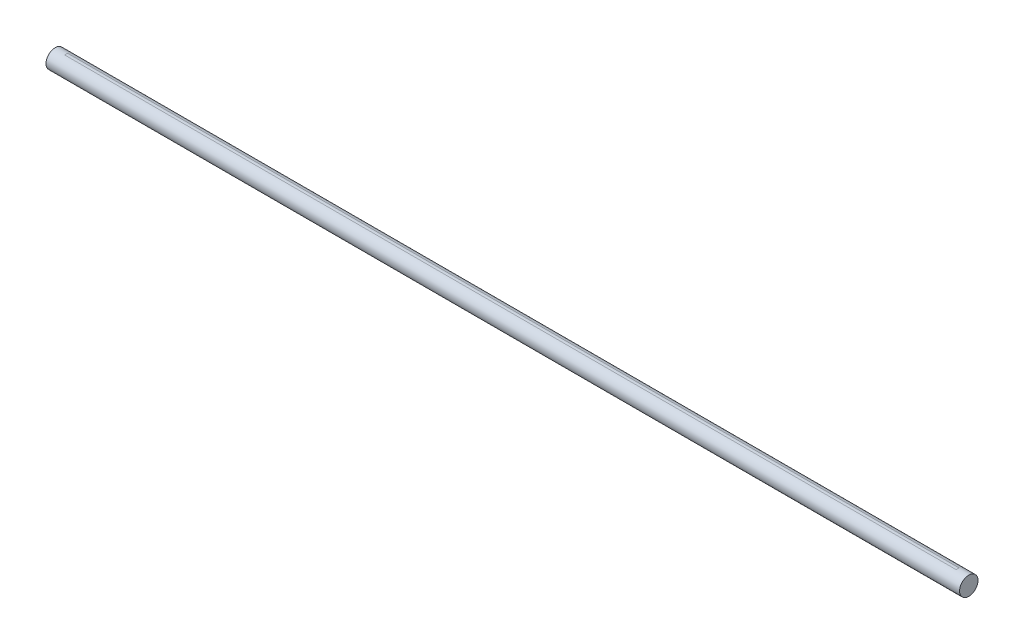
SolidWorks part; units mm, degrees
material "Custom Teakwood"
ref_plane "Front Plane" through (0, 0, 0) normal (0, 0, 1) x (1, 0, 0)
ref_plane "Top Plane" through (0, 0, 0) normal (0, 1, 0) x (1, 0, 0)
ref_plane "Right Plane" through (0, 0, 0) normal (1, 0, 0) x (0, 0, -1)
sketch "Sketch1" plane through (0, 0, 0) normal (1, 0, 0) x (0, 0, -1)
  circle A0 centre (0, 0) radius 15.875
  dimension "D1" = 31.75
extrude "Boss-Extrude1" add sketch "Sketch1" against normal blind 1574.8
sketch "Sketch3" plane through (0, 0, 0) normal (0, 1, 0) x (1, 0, 0)
  line L0 (-1555.75, 2.54) -> (-19.05, 2.54)
  line L1 (-1555.75, 2.54) -> (-1555.75, -2.54)
  line L2 (-1555.75, -2.54) -> (-19.05, -2.54)
  line L3 (-19.05, 2.54) -> (-19.05, -2.54)
  line L4 (-1574.8, 15.875) -> (-1574.8, -15.875) construction
  point P6 (-19.05, 0)
  dimension "D1" = 5.08
  dimension "D2" = 1536.7
  dimension "D3" = 19.05
split line "Split Line2"
